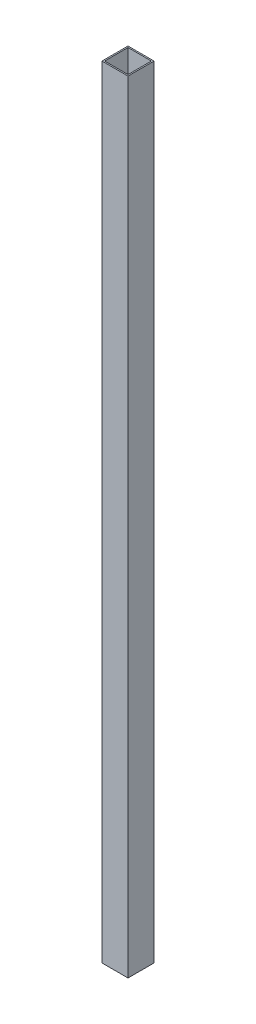
SolidWorks part; units mm, degrees
ref_plane "前视基准面" through (0, 0, 0) normal (0, 0, 1) x (1, 0, 0)
ref_plane "上视基准面" through (0, 0, 0) normal (0, 1, 0) x (1, 0, 0)
ref_plane "右视基准面" through (0, 0, 0) normal (1, 0, 0) x (0, 0, -1)
sketch "草图1" plane through (0, 0, 0) normal (0, 1, 0) x (1, 0, 0)
  line L1 (-10, 10) -> (10, 10)
  line L2 (-10, 10) -> (-10, -10)
  line L3 (-10, -10) -> (10, -10)
  line L4 (10, 10) -> (10, -10)
  line L5 (0, -10) -> (0, 10) construction
  line L6 (-10, 0) -> (10, 0) construction
  line L7 (-9, 9) -> (9, 9)
  line L8 (-9, 9) -> (-9, -9)
  line L9 (-9, -9) -> (9, -9)
  line L10 (9, 9) -> (9, -9)
  line L11 (0, -9) -> (0, 9) construction
  line L12 (-9, 0) -> (9, 0) construction
  point P0 (0, 0)
  point P4 (0, 0)
  dimension "D1" = 20
  dimension "D2" = 20
  dimension "D3" = 18
  dimension "D4" = 18
extrude "凸台-拉伸1" add sketch "草图1" along normal blind 600
